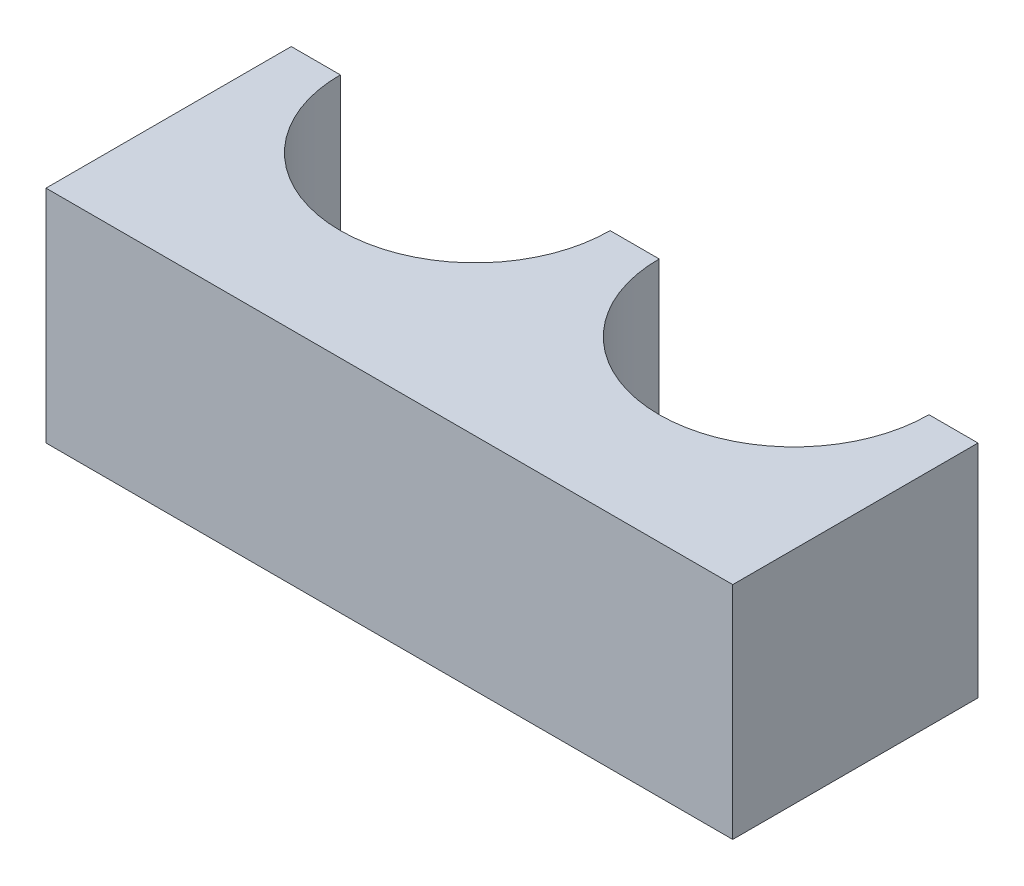
SolidWorks part; units mm, degrees
ref_plane "Front Plane" through (0, 0, 0) normal (0, 0, 1) x (1, 0, 0)
ref_plane "Top Plane" through (0, 0, 0) normal (0, 1, 0) x (1, 0, 0)
ref_plane "Right Plane" through (0, 0, 0) normal (1, 0, 0) x (0, 0, -1)
sketch "Sketch1" plane through (0, 0, 0) normal (0, 0, 1) x (1, 0, 0)
  line L1 (-14000, -4500) -> (14000, -4500)
  line L2 (-14000, -4500) -> (-14000, 4500)
  line L3 (-14000, 4500) -> (14000, 4500)
  line L4 (14000, -4500) -> (14000, 4500)
  line L5 (-14000, -4500) -> (14000, 4500) construction
  line L6 (-14000, 4500) -> (14000, -4500) construction
  point P0 (0, 0)
  dimension "D1" = 28000
  dimension "D2" = 9000
extrude "Boss-Extrude1" add sketch "Sketch1" along normal blind 10000
sketch "Sketch2" plane through (0, -4500, 0) normal (0, -1, 0) x (1, 0, 0)
  line L0 (-14000, 0) -> (14000, 0) construction
  line L1 (-14000, 10000) -> (-14000, 0) construction
  line L2 (-12000, 0) -> (-1000, 0)
  line L3 (1000, 0) -> (12000, 0)
  line L4 (-12000, 0) -> (1000, 0) construction
  arc A0 (-12000, 0) -> (-1000, 0) centre (-6500, 0) cw
  arc A1 (1000, 0) -> (12000, 0) centre (6500, 0) cw
  dimension "D1" = 2000
  dimension "D2" = 11000
  dimension "D5" = 13000
  dimension "D4" = 2
extrude "Cut-Extrude1" cut sketch "Sketch2" against normal up to next
